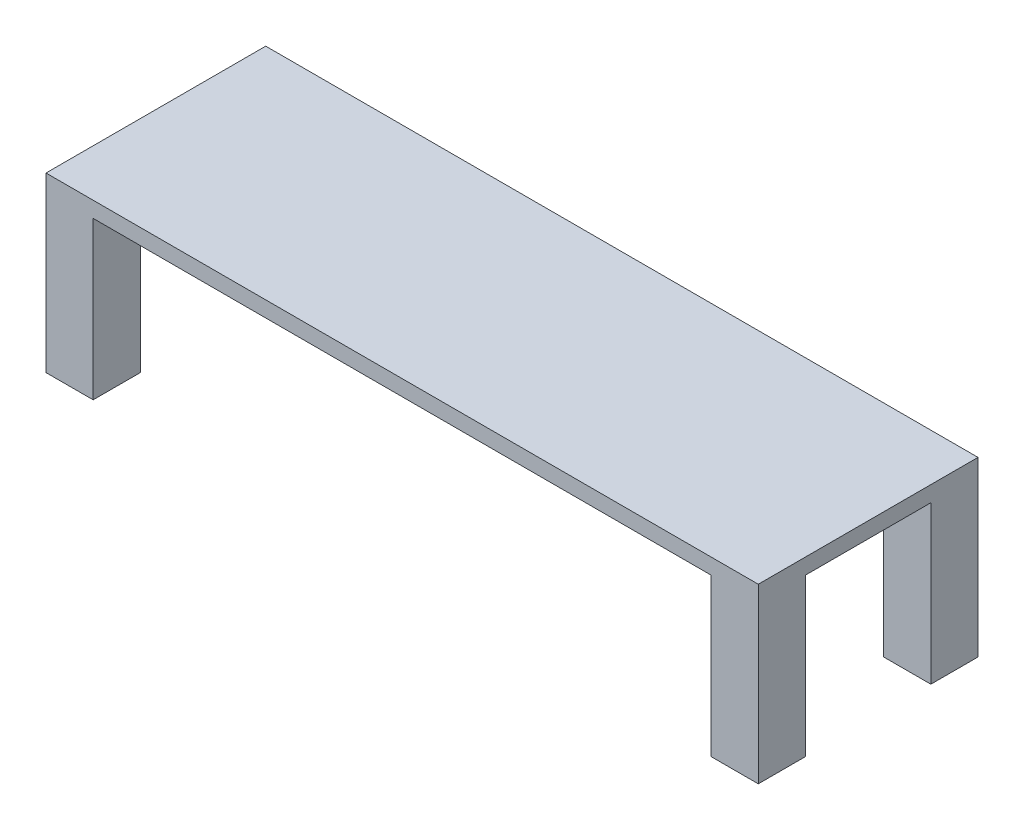
SolidWorks part; units mm, degrees
ref_plane "Plan de face" through (0, 0, 0) normal (0, 0, 1) x (1, 0, 0)
ref_plane "Plan de dessus" through (0, 0, 0) normal (0, 1, 0) x (1, 0, 0)
ref_plane "Plan de droite" through (0, 0, 0) normal (1, 0, 0) x (0, 0, -1)
sketch "Esquisse1" plane through (0, 0, 0) normal (0, 1, 0) x (1, 0, 0)
  line L1 (-113.3, -27.45) -> (-113.3, -19.95)
  line L3 (-113.3, -74.85) -> (-113.3, -82.35)
  line L4 (-113.3, -19.95) -> (-98.3, -19.95)
  line L5 (-98.3, -19.95) -> (-98.3, -34.95)
  line L6 (-98.3, -34.95) -> (-113.3, -34.95)
  line L7 (-113.3, -34.95) -> (-113.3, -27.45)
  line L8 (-98.3, -74.85) -> (-113.3, -74.85)
  line L9 (-98.3, -89.85) -> (-98.3, -74.85)
  line L10 (-113.3, -89.85) -> (-98.3, -89.85)
  line L11 (-113.3, -82.35) -> (-113.3, -89.85)
  line L12 (98.3, -74.85) -> (113.3, -74.85)
  line L13 (98.3, -89.85) -> (98.3, -74.85)
  line L14 (113.3, -89.85) -> (98.3, -89.85)
  line L15 (113.3, -82.35) -> (113.3, -89.85)
  line L16 (113.3, -74.85) -> (113.3, -82.35)
  line L17 (113.3, -34.95) -> (113.3, -27.45)
  line L18 (98.3, -34.95) -> (113.3, -34.95)
  line L19 (98.3, -19.95) -> (98.3, -34.95)
  line L20 (113.3, -19.95) -> (98.3, -19.95)
  line L21 (113.3, -27.45) -> (113.3, -19.95)
  circle A0 centre (-105.8, -27.45) radius 2
  circle A2 centre (-105.8, -82.35) radius 2
  circle A3 centre (105.8, -82.35) radius 2
  circle A4 centre (105.8, -27.45) radius 2
  point P1 (0, 0)
  point P4 (0, 0)
  point P10 (-106.3727, -71.7223)
  point P14 (-105.8, -27.45)
  dimension "D1" = 211.6
  dimension "D2" = 54.9
  dimension "D3" = 7.5
  dimension "D4" = 7.5
  dimension "D5" = 7.5
  dimension "D6" = 7.5
  dimension "D7" = 7.5
  dimension "D8" = 7.5
  dimension "D9" = 7.5
  dimension "D10" = 7.5
extrude "Boss.-Extru.1" add sketch "Esquisse1" along normal blind 50
sketch "Esquisse2" plane through (0, 50, 0) normal (0, 1, 0) x (1, 0, 0)
  line L0 (-113.3, -19.95) -> (113.3, -19.95)
  line L3 (113.3, -19.95) -> (113.3, -89.85)
  line L4 (113.3, -89.85) -> (113.3, -74.85) construction
  line L5 (98.3, -89.85) -> (113.3, -89.85) construction
  line L6 (113.3, -89.85) -> (-113.3, -89.85)
  line L7 (-113.3, -89.85) -> (-113.3, -19.95)
extrude "Boss.-Extru.2" add sketch "Esquisse2" along normal blind 5
